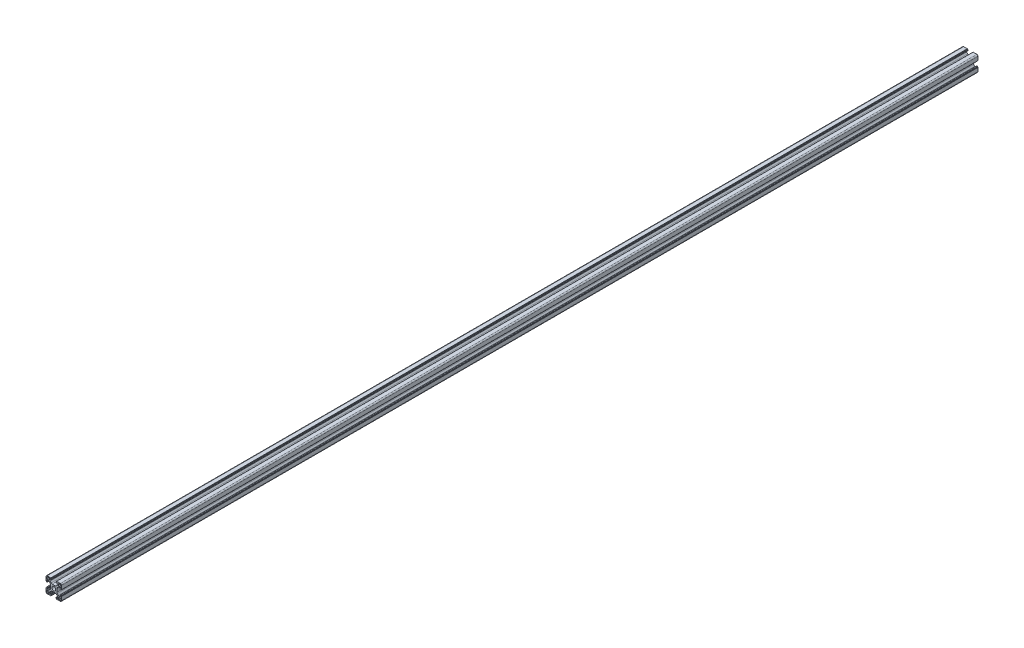
SolidWorks part; units mm, degrees
material "1060 Сплав"
ref_plane "Спереди" through (0, 0, 0) normal (0, 0, 1) x (1, 0, 0)
ref_plane "Сверху" through (0, 0, 0) normal (0, 1, 0) x (1, 0, 0)
ref_plane "Справа" through (0, 0, 0) normal (1, 0, 0) x (0, 0, -1)
sketch "Эскиз1" plane through (0, 0, 0) normal (0, 0, 1) x (1, 0, 0)
  line L0 (-22.0052, 70.3096) -> (-25.0052, 67.3096) construction
  line L1 (-31.1052, 65.2096) -> (-29.2064, 65.2096)
  line L2 (-31.1052, 61.2096) -> (-21.1052, 71.2096) construction
  line L3 (-23.5052, 68.8096) -> (-25.0052, 70.3096) construction
  line L4 (-27.7922, 65.7954) -> (-26.4909, 67.0967)
  line L5 (-24.2052, 67.3096) -> (-22.8052, 67.3096)
  line L6 (-25.0052, 68.1096) -> (-25.0052, 69.5096)
  line L7 (-22.8052, 70.3096) -> (-24.2052, 70.3096)
  line L8 (-25.9052, 69.4096) -> (-25.9052, 68.5109)
  line L9 (-27.3419, 69.2829) -> (-26.8616, 69.7632)
  line L10 (-27.9052, 70.7587) -> (-27.4052, 70.7587)
  line L11 (-27.5187, 69.2096) -> (-27.8052, 69.2096)
  line L12 (-26.508, 69.9096) -> (-26.4052, 69.9096)
  line L13 (-27.4052, 71.0596) -> (-27.4052, 70.7587)
  line L14 (-28.0552, 70.6087) -> (-28.0552, 69.4596)
  line L15 (-22.6052, 71.2096) -> (-27.2552, 71.2096)
  line L16 (-22.0052, 69.5096) -> (-22.0052, 68.1096)
  line L17 (-21.1052, 69.7096) -> (-21.1052, 65.0596)
  line L18 (-21.7061, 64.2596) -> (-22.8552, 64.2596)
  line L19 (-21.2552, 64.9096) -> (-21.5561, 64.9096)
  line L20 (-22.4052, 65.8068) -> (-22.4052, 65.9096)
  line L21 (-23.1052, 64.7961) -> (-23.1052, 64.5096)
  line L22 (-21.5561, 64.4096) -> (-21.5561, 64.9096)
  line L23 (-23.0319, 64.9729) -> (-22.5516, 65.4532)
  line L24 (-22.9052, 66.4096) -> (-23.8039, 66.4096)
  line L25 (-26.5194, 64.5226) -> (-25.2181, 65.8239)
  line L26 (-27.1052, 61.2096) -> (-27.1052, 63.1084)
  line L27 (-27.1052, 61.2096) -> (-27.1052, 59.3109)
  line L28 (-26.5194, 57.8967) -> (-25.2181, 56.5954)
  line L29 (-25.0052, 54.3096) -> (-25.0052, 52.9096)
  line L30 (-24.2052, 55.1096) -> (-22.8052, 55.1096)
  line L31 (-22.0052, 52.9096) -> (-22.0052, 54.3096)
  line L32 (-22.9052, 56.0096) -> (-23.8039, 56.0096)
  line L33 (-23.0319, 57.4464) -> (-22.5516, 56.9661)
  line L34 (-21.5561, 58.0096) -> (-21.5561, 57.5096)
  line L35 (-23.1052, 57.6232) -> (-23.1052, 57.9096)
  line L36 (-22.4052, 56.6125) -> (-22.4052, 56.5096)
  line L37 (-21.2552, 57.5096) -> (-21.5561, 57.5096)
  line L38 (-21.7061, 58.1596) -> (-22.8552, 58.1596)
  line L39 (-21.1052, 52.7096) -> (-21.1052, 57.3596)
  line L40 (-22.8052, 52.1096) -> (-24.2052, 52.1096)
  line L41 (-22.6052, 51.2096) -> (-27.2552, 51.2096)
  line L42 (-28.0552, 51.8106) -> (-28.0552, 52.9596)
  line L43 (-27.4052, 51.3596) -> (-27.4052, 51.6606)
  line L44 (-26.508, 52.5096) -> (-26.4052, 52.5096)
  line L45 (-27.5187, 53.2096) -> (-27.8052, 53.2096)
  line L46 (-27.9052, 51.6606) -> (-27.4052, 51.6606)
  line L47 (-27.3419, 53.1364) -> (-26.8616, 52.6561)
  line L48 (-25.9052, 53.0096) -> (-25.9052, 53.9084)
  line L49 (-27.7922, 56.6239) -> (-26.4909, 55.3226)
  line L50 (-31.1052, 57.2096) -> (-29.2064, 57.2096)
  line L51 (-22.0052, 52.1096) -> (-25.0052, 55.1096) construction
  line L52 (-31.1052, 61.2096) -> (-21.1052, 51.2096) construction
  line L53 (-23.5052, 53.6096) -> (-22.0052, 55.1096) construction
  line L54 (-31.1052, 57.2096) -> (-33.0039, 57.2096)
  line L55 (-34.4181, 56.6239) -> (-35.7194, 55.3226)
  line L56 (-38.0052, 55.1096) -> (-39.4052, 55.1096)
  line L57 (-37.2052, 54.3096) -> (-37.2052, 52.9096)
  line L58 (-39.4052, 52.1096) -> (-38.0052, 52.1096)
  line L59 (-36.3052, 53.0096) -> (-36.3052, 53.9084)
  line L60 (-34.8684, 53.1364) -> (-35.3487, 52.6561)
  line L61 (-34.3052, 51.6606) -> (-34.8052, 51.6606)
  line L62 (-34.6916, 53.2096) -> (-34.4052, 53.2096)
  line L63 (-35.7023, 52.5096) -> (-35.8052, 52.5096)
  line L64 (-34.8052, 51.3596) -> (-34.8052, 51.6606)
  line L65 (-34.1552, 51.8106) -> (-34.1552, 52.9596)
  line L66 (-39.6052, 51.2096) -> (-34.9552, 51.2096)
  line L67 (-40.2052, 52.9096) -> (-40.2052, 54.3096)
  line L68 (-41.1052, 52.7096) -> (-41.1052, 57.3596)
  line L69 (-40.5042, 58.1596) -> (-39.3552, 58.1596)
  line L70 (-40.9552, 57.5096) -> (-40.6542, 57.5096)
  line L71 (-39.8052, 56.6125) -> (-39.8052, 56.5096)
  line L72 (-39.1052, 57.6232) -> (-39.1052, 57.9096)
  line L73 (-40.6542, 58.0096) -> (-40.6542, 57.5096)
  line L74 (-39.1784, 57.4464) -> (-39.6587, 56.9661)
  line L75 (-39.3052, 56.0096) -> (-38.4064, 56.0096)
  line L76 (-35.6909, 57.8967) -> (-36.9922, 56.5954)
  line L77 (-35.1052, 61.2096) -> (-35.1052, 59.3109)
  line L78 (-40.2052, 52.1096) -> (-37.2052, 55.1096) construction
  line L79 (-31.1052, 61.2096) -> (-41.1052, 51.2096) construction
  line L80 (-38.7052, 53.6096) -> (-37.2052, 52.1096) construction
  line L81 (-35.1052, 61.2096) -> (-35.1052, 63.1084)
  line L82 (-35.6909, 64.5226) -> (-36.9922, 65.8239)
  line L83 (-37.2052, 68.1096) -> (-37.2052, 69.5096)
  line L84 (-38.0052, 67.3096) -> (-39.4052, 67.3096)
  line L85 (-40.2052, 69.5096) -> (-40.2052, 68.1096)
  line L86 (-39.3052, 66.4096) -> (-38.4064, 66.4096)
  line L87 (-39.1784, 64.9729) -> (-39.6587, 65.4532)
  line L88 (-40.6542, 64.4096) -> (-40.6542, 64.9096)
  line L89 (-39.1052, 64.7961) -> (-39.1052, 64.5096)
  line L90 (-39.8052, 65.8068) -> (-39.8052, 65.9096)
  line L91 (-40.9552, 64.9096) -> (-40.6542, 64.9096)
  line L92 (-40.5042, 64.2596) -> (-39.3552, 64.2596)
  line L93 (-41.1052, 69.7096) -> (-41.1052, 65.0596)
  line L94 (-39.4052, 70.3096) -> (-38.0052, 70.3096)
  line L95 (-39.6052, 71.2096) -> (-34.9552, 71.2096)
  line L96 (-34.1552, 70.6087) -> (-34.1552, 69.4596)
  line L97 (-34.8052, 71.0596) -> (-34.8052, 70.7587)
  line L98 (-35.7023, 69.9096) -> (-35.8052, 69.9096)
  line L99 (-34.6916, 69.2096) -> (-34.4052, 69.2096)
  line L100 (-34.3052, 70.7587) -> (-34.8052, 70.7587)
  line L101 (-34.8684, 69.2829) -> (-35.3487, 69.7632)
  line L102 (-36.3052, 69.4096) -> (-36.3052, 68.5109)
  line L103 (-34.4181, 65.7954) -> (-35.7194, 67.0967)
  line L104 (-31.1052, 65.2096) -> (-33.0039, 65.2096)
  line L105 (-42.8692, 61.2096) -> (-19.6008, 61.2096) construction
  line L106 (-40.2052, 70.3096) -> (-37.2052, 67.3096) construction
  line L107 (-31.1052, 49.1232) -> (-31.1052, 71.9286) construction
  line L108 (-31.1052, 61.2096) -> (-41.1052, 71.2096) construction
  line L109 (-38.7052, 68.8096) -> (-40.2052, 67.3096) construction
  arc A0 (-22.0052, 69.5096) -> (-22.8052, 70.3096) centre (-22.8052, 69.5096) ccw
  arc A1 (-24.2052, 70.3096) -> (-25.0052, 69.5096) centre (-24.2052, 69.5096) ccw
  arc A2 (-24.2052, 67.3096) -> (-25.0052, 68.1096) centre (-24.2052, 68.1096) cw
  arc A3 (-22.6052, 71.2096) -> (-21.1052, 69.7096) centre (-22.6052, 69.7096) cw
  arc A4 (-27.9052, 70.7587) -> (-28.0552, 70.6087) centre (-27.9052, 70.6087) ccw
  arc A5 (-27.2552, 71.2096) -> (-27.4052, 71.0596) centre (-27.2552, 71.0596) ccw
  arc A6 (-27.5187, 69.2096) -> (-27.3419, 69.2829) centre (-27.5187, 69.4596) ccw
  arc A7 (-27.8052, 69.2096) -> (-28.0552, 69.4596) centre (-27.8052, 69.4596) cw
  arc A8 (-26.8616, 69.7632) -> (-26.508, 69.9096) centre (-26.508, 69.4096) cw
  arc A9 (-26.4052, 69.9096) -> (-25.9052, 69.4096) centre (-26.4052, 69.4096) cw
  arc A10 (-28.6052, 61.2096) -> (-31.1052, 63.7096) centre (-31.1052, 61.2096) ccw
  arc A11 (-29.2064, 65.2096) -> (-27.7922, 65.7954) centre (-29.2064, 67.2096) ccw
  arc A12 (-25.9052, 68.5109) -> (-26.4909, 67.0967) centre (-27.9052, 68.5109) cw
  arc A13 (-22.0052, 68.1096) -> (-22.8052, 67.3096) centre (-22.8052, 68.1096) cw
  arc A14 (-22.4052, 65.9096) -> (-22.9052, 66.4096) centre (-22.9052, 65.9096) ccw
  arc A15 (-22.5516, 65.4532) -> (-22.4052, 65.8068) centre (-22.9052, 65.8068) ccw
  arc A16 (-23.1052, 64.5096) -> (-22.8552, 64.2596) centre (-22.8552, 64.5096) ccw
  arc A17 (-23.1052, 64.7961) -> (-23.0319, 64.9729) centre (-22.8552, 64.7961) cw
  arc A18 (-21.1052, 65.0596) -> (-21.2552, 64.9096) centre (-21.2552, 65.0596) cw
  arc A19 (-21.5561, 64.4096) -> (-21.7061, 64.2596) centre (-21.7061, 64.4096) cw
  arc A20 (-23.8039, 66.4096) -> (-25.2181, 65.8239) centre (-23.8039, 64.4096) ccw
  arc A21 (-27.1052, 63.1084) -> (-26.5194, 64.5226) centre (-25.1052, 63.1084) cw
  arc A22 (-22.8052, 52.1096) -> (-22.0052, 52.9096) centre (-22.8052, 52.9096) ccw
  arc A23 (-22.0052, 54.3096) -> (-22.8052, 55.1096) centre (-22.8052, 54.3096) ccw
  arc A24 (-25.0052, 54.3096) -> (-24.2052, 55.1096) centre (-24.2052, 54.3096) cw
  arc A25 (-21.1052, 52.7096) -> (-22.6052, 51.2096) centre (-22.6052, 52.7096) cw
  arc A26 (-21.5561, 58.0096) -> (-21.7061, 58.1596) centre (-21.7061, 58.0096) ccw
  arc A27 (-21.1052, 57.3596) -> (-21.2552, 57.5096) centre (-21.2552, 57.3596) ccw
  arc A28 (-23.1052, 57.6232) -> (-23.0319, 57.4464) centre (-22.8552, 57.6232) ccw
  arc A29 (-23.1052, 57.9096) -> (-22.8552, 58.1596) centre (-22.8552, 57.9096) cw
  arc A30 (-22.5516, 56.9661) -> (-22.4052, 56.6125) centre (-22.9052, 56.6125) cw
  arc A31 (-22.4052, 56.5096) -> (-22.9052, 56.0096) centre (-22.9052, 56.5096) cw
  arc A32 (-31.1052, 58.7096) -> (-28.6052, 61.2096) centre (-31.1052, 61.2096) ccw
  arc A33 (-27.1052, 59.3109) -> (-26.5194, 57.8967) centre (-25.1052, 59.3109) ccw
  arc A34 (-23.8039, 56.0096) -> (-25.2181, 56.5954) centre (-23.8039, 58.0096) cw
  arc A35 (-24.2052, 52.1096) -> (-25.0052, 52.9096) centre (-24.2052, 52.9096) cw
  arc A36 (-26.4052, 52.5096) -> (-25.9052, 53.0096) centre (-26.4052, 53.0096) ccw
  arc A37 (-26.8616, 52.6561) -> (-26.508, 52.5096) centre (-26.508, 53.0096) ccw
  arc A38 (-27.8052, 53.2096) -> (-28.0552, 52.9596) centre (-27.8052, 52.9596) ccw
  arc A39 (-27.5187, 53.2096) -> (-27.3419, 53.1364) centre (-27.5187, 52.9596) cw
  arc A40 (-27.2552, 51.2096) -> (-27.4052, 51.3596) centre (-27.2552, 51.3596) cw
  arc A41 (-27.9052, 51.6606) -> (-28.0552, 51.8106) centre (-27.9052, 51.8106) cw
  arc A42 (-25.9052, 53.9084) -> (-26.4909, 55.3226) centre (-27.9052, 53.9084) ccw
  arc A43 (-29.2064, 57.2096) -> (-27.7922, 56.6239) centre (-29.2064, 55.2096) cw
  arc A44 (-40.2052, 52.9096) -> (-39.4052, 52.1096) centre (-39.4052, 52.9096) ccw
  arc A45 (-38.0052, 52.1096) -> (-37.2052, 52.9096) centre (-38.0052, 52.9096) ccw
  arc A46 (-38.0052, 55.1096) -> (-37.2052, 54.3096) centre (-38.0052, 54.3096) cw
  arc A47 (-39.6052, 51.2096) -> (-41.1052, 52.7096) centre (-39.6052, 52.7096) cw
  arc A48 (-34.3052, 51.6606) -> (-34.1552, 51.8106) centre (-34.3052, 51.8106) ccw
  arc A49 (-34.9552, 51.2096) -> (-34.8052, 51.3596) centre (-34.9552, 51.3596) ccw
  arc A50 (-34.6916, 53.2096) -> (-34.8684, 53.1364) centre (-34.6916, 52.9596) ccw
  arc A51 (-34.4052, 53.2096) -> (-34.1552, 52.9596) centre (-34.4052, 52.9596) cw
  arc A52 (-35.3487, 52.6561) -> (-35.7023, 52.5096) centre (-35.7023, 53.0096) cw
  arc A53 (-35.8052, 52.5096) -> (-36.3052, 53.0096) centre (-35.8052, 53.0096) cw
  arc A54 (-33.6052, 61.2096) -> (-31.1052, 58.7096) centre (-31.1052, 61.2096) ccw
  arc A55 (-33.0039, 57.2096) -> (-34.4181, 56.6239) centre (-33.0039, 55.2096) ccw
  arc A56 (-36.3052, 53.9084) -> (-35.7194, 55.3226) centre (-34.3052, 53.9084) cw
  arc A57 (-40.2052, 54.3096) -> (-39.4052, 55.1096) centre (-39.4052, 54.3096) cw
  arc A58 (-39.8052, 56.5096) -> (-39.3052, 56.0096) centre (-39.3052, 56.5096) ccw
  arc A59 (-39.6587, 56.9661) -> (-39.8052, 56.6125) centre (-39.3052, 56.6125) ccw
  arc A60 (-39.1052, 57.9096) -> (-39.3552, 58.1596) centre (-39.3552, 57.9096) ccw
  arc A61 (-39.1052, 57.6232) -> (-39.1784, 57.4464) centre (-39.3552, 57.6232) cw
  arc A62 (-41.1052, 57.3596) -> (-40.9552, 57.5096) centre (-40.9552, 57.3596) cw
  arc A63 (-40.6542, 58.0096) -> (-40.5042, 58.1596) centre (-40.5042, 58.0096) cw
  arc A64 (-38.4064, 56.0096) -> (-36.9922, 56.5954) centre (-38.4064, 58.0096) ccw
  arc A65 (-35.1052, 59.3109) -> (-35.6909, 57.8967) centre (-37.1052, 59.3109) cw
  arc A66 (-39.4052, 70.3096) -> (-40.2052, 69.5096) centre (-39.4052, 69.5096) ccw
  arc A67 (-40.2052, 68.1096) -> (-39.4052, 67.3096) centre (-39.4052, 68.1096) ccw
  arc A68 (-37.2052, 68.1096) -> (-38.0052, 67.3096) centre (-38.0052, 68.1096) cw
  arc A69 (-41.1052, 69.7096) -> (-39.6052, 71.2096) centre (-39.6052, 69.7096) cw
  arc A70 (-40.6542, 64.4096) -> (-40.5042, 64.2596) centre (-40.5042, 64.4096) ccw
  arc A71 (-41.1052, 65.0596) -> (-40.9552, 64.9096) centre (-40.9552, 65.0596) ccw
  arc A72 (-39.1052, 64.7961) -> (-39.1784, 64.9729) centre (-39.3552, 64.7961) ccw
  arc A73 (-39.1052, 64.5096) -> (-39.3552, 64.2596) centre (-39.3552, 64.5096) cw
  arc A74 (-39.6587, 65.4532) -> (-39.8052, 65.8068) centre (-39.3052, 65.8068) cw
  arc A75 (-39.8052, 65.9096) -> (-39.3052, 66.4096) centre (-39.3052, 65.9096) cw
  arc A76 (-31.1052, 63.7096) -> (-33.6052, 61.2096) centre (-31.1052, 61.2096) ccw
  arc A77 (-35.1052, 63.1084) -> (-35.6909, 64.5226) centre (-37.1052, 63.1084) ccw
  arc A78 (-38.4064, 66.4096) -> (-36.9922, 65.8239) centre (-38.4064, 64.4096) cw
  arc A79 (-38.0052, 70.3096) -> (-37.2052, 69.5096) centre (-38.0052, 69.5096) cw
  arc A80 (-35.8052, 69.9096) -> (-36.3052, 69.4096) centre (-35.8052, 69.4096) ccw
  arc A81 (-35.3487, 69.7632) -> (-35.7023, 69.9096) centre (-35.7023, 69.4096) ccw
  arc A82 (-34.4052, 69.2096) -> (-34.1552, 69.4596) centre (-34.4052, 69.4596) ccw
  arc A83 (-34.6916, 69.2096) -> (-34.8684, 69.2829) centre (-34.6916, 69.4596) cw
  arc A84 (-34.9552, 71.2096) -> (-34.8052, 71.0596) centre (-34.9552, 71.0596) cw
  arc A85 (-34.3052, 70.7587) -> (-34.1552, 70.6087) centre (-34.3052, 70.6087) cw
  arc A86 (-36.3052, 68.5109) -> (-35.7194, 67.0967) centre (-34.3052, 68.5109) ccw
  arc A87 (-33.0039, 65.2096) -> (-34.4181, 65.7954) centre (-33.0039, 67.2096) cw
  point P0 (-31.1052, 61.2096)
  point P9 (-31.1052, 61.2096)
  point P40 (-22.4052, 64.9096)
  point P93 (-27.4052, 52.5096)
  point P144 (-27.4052, 69.9096)
  point P152 (-22.4052, 57.5096)
  point P153 (-31.1052, 57.2854)
  point P154 (-31.1052, 61.2096)
  point P189 (-39.8052, 57.5096)
  point P228 (-34.8052, 52.5096)
  point P229 (-35.0294, 61.2096)
  point P230 (-31.1052, 61.2096)
  point P268 (-34.8052, 69.9096)
  point P273 (-27.1809, 61.2096)
  point P306 (-39.8052, 64.9096)
  point P307 (-31.1052, 65.1339)
  point P309 (-31.1052, 61.2096)
  dimension "D3" = 5
  dimension "D6" = 2
  dimension "D1" = 2
  dimension "D2" = 6
  dimension "D4" = 4
  dimension "D5" = 0.9
extrude "Бобышка-Вытянуть1" add sketch "Эскиз1" along normal blind 1180
